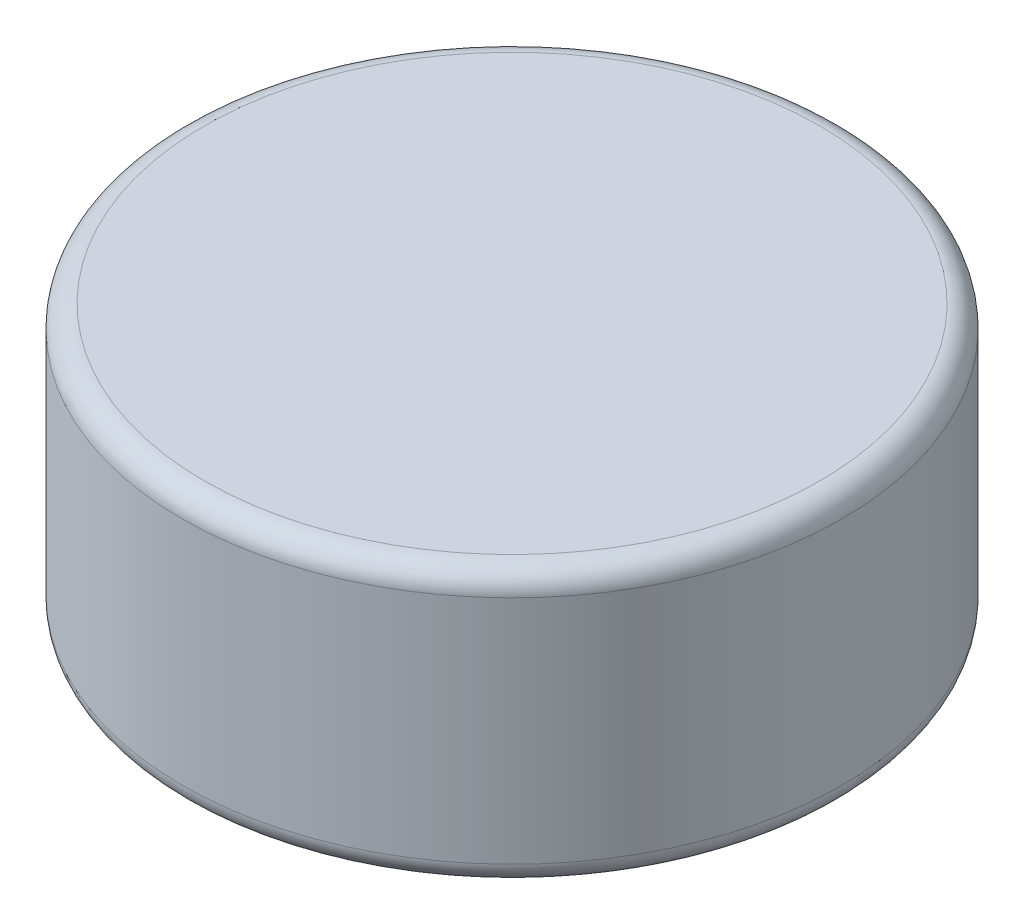
SolidWorks part; units mm, degrees
material "Cobalt"
ref_plane "Front Plane" through (0, 0, 0) normal (0, 0, 1) x (1, 0, 0)
ref_plane "Top Plane" through (0, 0, 0) normal (0, 1, 0) x (1, 0, 0)
ref_plane "Right Plane" through (0, 0, 0) normal (1, 0, 0) x (0, 0, -1)
sketch "Sketch1" plane through (0, 0, 0) normal (0, 1, 0) x (1, 0, 0)
  circle A0 centre (0, 0) radius 3
  dimension "D1" = 6
extrude "Boss-Extrude1" add sketch "Sketch1" along normal mid plane 2.5
fillet "Fillet1" radius 0.2 2 edges at (0, -1.25, 3) (0, 1.25, 3)
sketch "Sketch2" plane through (0, 0, 0) normal (1, 0, 0) x (0, 0, -1)
  line L0 (0, 2.102) -> (0, -2.102) construction
  point P2 (0, 0)
ref_plane "Plane1" through (0, -0.25, 0) normal (0, 1, 0) x (1, 0, 0)
ref_plane "Plane2" through (0, 0.25, 0) normal (0, 1, 0) x (1, 0, 0)
